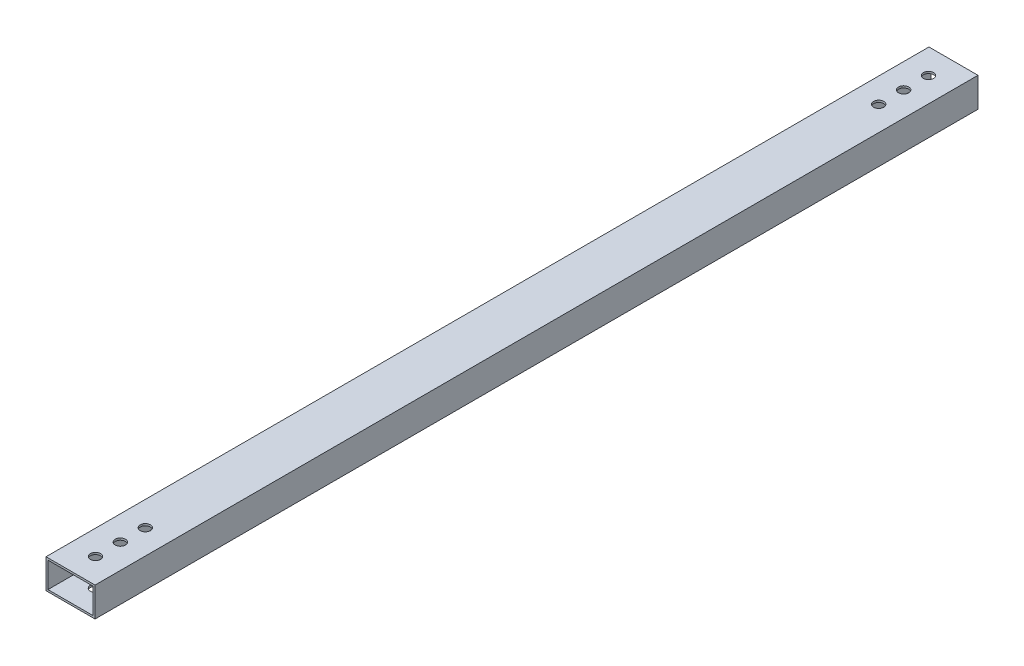
SolidWorks part; units mm, degrees
material "6063-O, 押出棒 (SS)"
ref_plane "正面" through (0, 0, 0) normal (0, 0, 1) x (1, 0, 0)
ref_plane "平面" through (0, 0, 0) normal (0, 1, 0) x (1, 0, 0)
ref_plane "右側面" through (0, 0, 0) normal (1, 0, 0) x (0, 0, -1)
sketch "ｽｹｯﾁ1" plane through (0, 0, 0) normal (0, 0, 1) x (1, 0, 0)
  line L0 (-11.5, 6.5) -> (-11.5, -6.5)
  line L1 (-12.5, 7.5) -> (12.5, 7.5)
  line L2 (-12.5, 7.5) -> (-12.5, -7.5)
  line L3 (-12.5, -7.5) -> (12.5, -7.5)
  line L4 (12.5, 7.5) -> (12.5, -7.5)
  line L5 (-12.5, 7.5) -> (12.5, -7.5) construction
  line L6 (-12.5, -7.5) -> (12.5, 7.5) construction
  line L7 (-11.5, -6.5) -> (11.5, -6.5)
  line L8 (11.5, 6.5) -> (11.5, -6.5)
  line L9 (-11.5, 6.5) -> (11.5, 6.5)
  point P0 (0, 0)
  dimension "D1" = 15
  dimension "D2" = 25
  dimension "D3" = 1
extrude "ﾎﾞｽ - 押し出し1" add sketch "ｽｹｯﾁ1" along normal blind 450
sketch "ｽｹｯﾁ2" plane through (0, 7.5, 0) normal (0, 1, 0) x (1, 0, 0)
  line L0 (12.5, -450) -> (12.5, 0) construction
  circle A0 centre (0, -12.7) radius 2.6
  circle A2 centre (0, -25.4) radius 2.6
  circle A3 centre (0, -38.1) radius 2.6
  dimension "D1" = 5.2
  dimension "D3" = 12.5
  dimension "D7" = 5.2
  dimension "D8" = 12.7
  dimension "D10" = 5.2
  dimension "D11" = 5.2
  dimension "D12" = 12.7
  dimension "D13" = 12.5
  dimension "D2" = 12.7
  dimension "D9" = 12.5
extrude "ｶｯﾄ - 押し出し1" cut sketch "ｽｹｯﾁ2" against normal through all
ref_plane "平面1" through (0, 0, 225) normal (0, 0, -1) x (-1, 0, 0)
mirror "ﾐﾗｰ1" about plane through (0, 0, 225) normal (0, 0, -1) of "ｶｯﾄ - 押し出し1"
equation "\"length\"= \"pipelength@swerve_drive_coaxisial.Assembly\""
equation "\"D1@ﾎﾞｽ - 押し出し1\"=\"length\""
equation "\"D1@平面1\"=\"length\"/2"
